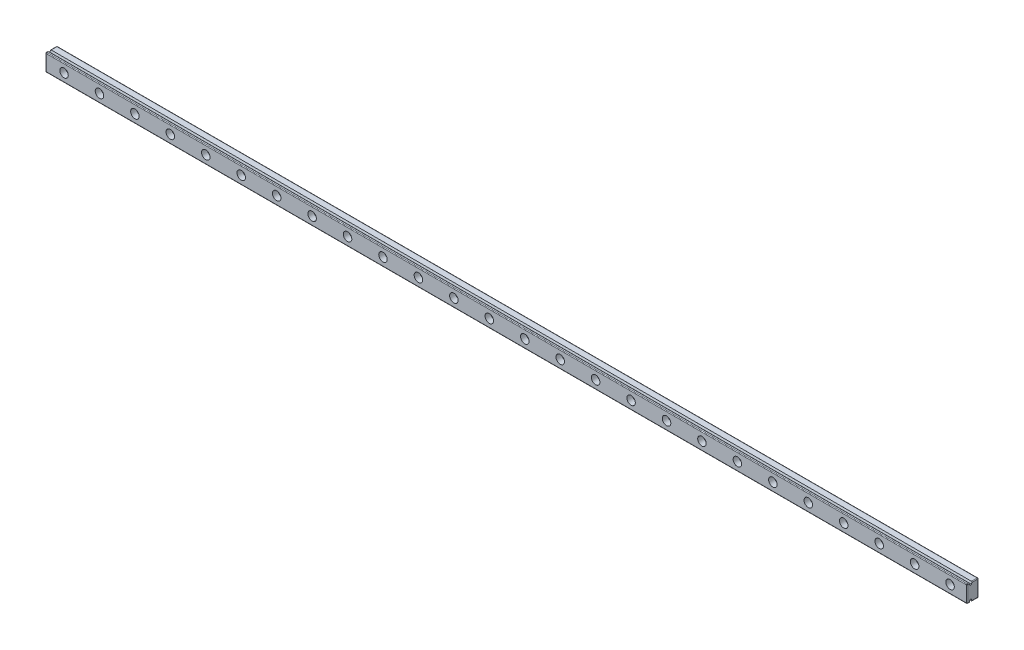
SolidWorks part; units mm, degrees
ref_plane "Front Plane" through (0, 0, 0) normal (0, 0, 1) x (1, 0, 0)
ref_plane "Top Plane" through (0, 0, 0) normal (0, 1, 0) x (1, 0, 0)
ref_plane "Right Plane" through (0, 0, 0) normal (1, 0, 0) x (0, 0, -1)
sketch "Sketch1" plane through (0, 0, 0) normal (1, 0, 0) x (0, 0, -1)
  line L0 (-0.5, 6) -> (4, 6)
  line L1 (-4, 6) -> (-2.5, 6)
  line L2 (-4, 6) -> (-4, -6)
  line L3 (-4, -6) -> (-2.5, -6)
  line L4 (4, 6) -> (4, -6)
  line L5 (-4, 6) -> (4, -6) construction
  line L6 (-4, -6) -> (4, 6) construction
  line L8 (-2.5, 6) -> (-2.5, 4.25)
  line L9 (-2.5, 4.25) -> (-0.5, 4.25)
  line L10 (-0.5, 6) -> (-0.5, 4.25)
  line L12 (-2.5, -6) -> (-2.5, -4.25)
  line L13 (-2.5, -4.25) -> (-0.5, -4.25)
  line L14 (-0.5, -6) -> (-0.5, -4.25)
  line L15 (-0.5, -6) -> (4, -6)
  point P0 (0, 0)
  dimension "D1" = 12
  dimension "D2" = 8
  dimension "D3" = 2
  dimension "D4" = 2
  dimension "D5" = 1.5
  dimension "D6" = 1.5
  dimension "D7" = 8.5
  dimension "D8" = 4.25
extrude "Boss-Extrude1" add sketch "Sketch1" along normal blind 650
sketch "Sketch2" plane through (0, 0, 4) normal (0, 0, 1) x (1, 0, 0)
  line L0 (0, 6) -> (0, -6) construction
  line L1 (0, 0) -> (650, 0) construction
  line L2 (650, 6) -> (650, -6) construction
  circle A0 centre (13, 0) radius 1.75
  circle A1 centre (38, 0) radius 1.75
  circle A2 centre (63, 0) radius 1.75
  circle A3 centre (88, 0) radius 1.75
  circle A4 centre (113, 0) radius 1.75
  circle A5 centre (138, 0) radius 1.75
  circle A6 centre (163, 0) radius 1.75
  circle A7 centre (188, 0) radius 1.75
  circle A8 centre (213, 0) radius 1.75
  circle A9 centre (238, 0) radius 1.75
  circle A10 centre (263, 0) radius 1.75
  circle A11 centre (288, 0) radius 1.75
  circle A12 centre (313, 0) radius 1.75
  circle A13 centre (338, 0) radius 1.75
  circle A14 centre (363, 0) radius 1.75
  circle A15 centre (388, 0) radius 1.75
  circle A16 centre (413, 0) radius 1.75
  circle A17 centre (438, 0) radius 1.75
  circle A18 centre (463, 0) radius 1.75
  circle A19 centre (488, 0) radius 1.75
  circle A21 centre (513, 0) radius 1.75
  circle A22 centre (538, 0) radius 1.75
  circle A23 centre (563, 0) radius 1.75
  circle A24 centre (588, 0) radius 1.75
  circle A25 centre (613, 0) radius 1.75
  circle A26 centre (638, 0) radius 1.75
  dimension "D1" = 3.5
  dimension "D4" = 25
  dimension "D5" = 3.5
  dimension "D6" = 3.5
  dimension "D7" = 3.5
  dimension "D8" = 3.5
  dimension "D9" = 3.5
  dimension "D10" = 3.5
  dimension "D11" = 3.5
  dimension "D12" = 25
  dimension "D13" = 25
  dimension "D14" = 25
  dimension "D15" = 25
  dimension "D16" = 25
  dimension "D17" = 25
  dimension "D18" = 3.5
  dimension "D19" = 3.5
  dimension "D20" = 3.5
  dimension "D21" = 25
  dimension "D22" = 25
  dimension "D23" = 25
  dimension "D24" = 25
  dimension "D2" = 13
  dimension "D3" = 16
extrude "Cut-Extrude1" cut sketch "Sketch2" against normal blind 10
sketch "Sketch3" plane through (0, 0, 4) normal (0, 0, 1) x (1, 0, 0)
  line L0 (0, 0) -> (650, 0) construction
  line L1 (650, 6) -> (650, -6) construction
  circle A0 centre (13, 0) radius 3
  circle A1 centre (38, 0) radius 3
  circle A2 centre (63, 0) radius 3
  circle A3 centre (88, 0) radius 3
  circle A4 centre (113, 0) radius 3
  circle A5 centre (138, 0) radius 3
  circle A6 centre (163, 0) radius 3
  circle A7 centre (188, 0) radius 3
  circle A8 centre (213, 0) radius 3
  circle A9 centre (238, 0) radius 3
  circle A10 centre (263, 0) radius 3
  circle A11 centre (288, 0) radius 3
  circle A12 centre (313, 0) radius 3
  circle A13 centre (338, 0) radius 3
  circle A14 centre (363, 0) radius 3
  circle A15 centre (388, 0) radius 3
  circle A16 centre (413, 0) radius 3
  circle A17 centre (438, 0) radius 3
  circle A18 centre (463, 0) radius 3
  circle A19 centre (488, 0) radius 3
  circle A20 centre (513, 0) radius 3
  circle A21 centre (538, 0) radius 3
  circle A22 centre (563, 0) radius 3
  circle A23 centre (588, 0) radius 3
  circle A24 centre (613, 0) radius 3
  circle A25 centre (638, 0) radius 3
  dimension "D1" = 6
  dimension "D3" = 25
  dimension "D4" = 6
  dimension "D5" = 6
  dimension "D6" = 6
  dimension "D7" = 6
  dimension "D8" = 6
  dimension "D9" = 6
  dimension "D10" = 6
  dimension "D11" = 6
  dimension "D12" = 6
  dimension "D13" = 6
  dimension "D2" = 16
extrude "Cut-Extrude2" cut sketch "Sketch3" against normal blind 4
chamfer "Chamfer1" distance 0.5 angle 74 4 edges at (325, -4.25, 2.5) (325, -4.25, 0.5) (325, 4.25, 2.5) (325, 4.25, 0.5)
fillet "Fillet1" radius 0.5 20 edges at (650, -6, -1.75) (650, 0, -4) (650, 6, -1.75) (650, 6, 3.25) (650, 0, 4) (650, -6, 3.25) (0, -6, 3.25) (0, -6, -1.75) (0, 0, -4) (0, 6, -1.75) (0, 6, 3.25) (0, 0, 4) (325, -4.25, 1) (325, -4.25, 2) (325, 4.25, 2) (325, 4.25, 1) (325, -6, 4) (325, 6, 4) (325, -6, -4) (325, 6, -4)
